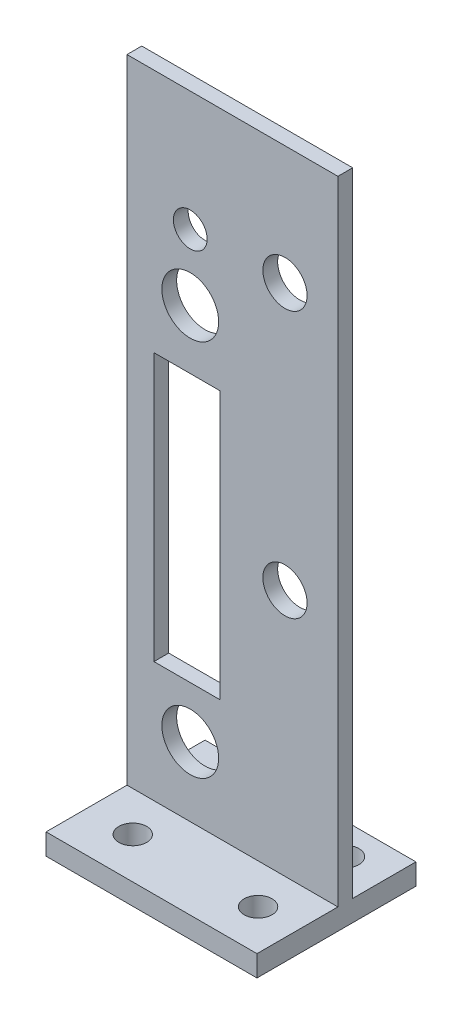
SolidWorks part; units mm, degrees
ref_plane "前视基准面" through (0, 0, 0) normal (0, 0, 1) x (1, 0, 0)
ref_plane "上视基准面" through (0, 0, 0) normal (0, 1, 0) x (1, 0, 0)
ref_plane "右视基准面" through (0, 0, 0) normal (1, 0, 0) x (0, 0, -1)
other "Configuration Table"
sketch "草图1" plane through (0, 0, 0) normal (0, 0, 1) x (1, 0, 0)
  line L1 (-23.3216, 41.8115) -> (26.6784, 41.8115)
  line L2 (-23.3216, 41.8115) -> (-23.3216, -108.1885)
  line L3 (-23.3216, -108.1885) -> (26.6784, -108.1885)
  line L4 (26.6784, 41.8115) -> (26.6784, -108.1885)
  dimension "D1" = 50
  dimension "D2" = 150
extrude "凸台-拉伸1" add sketch "草图1" along normal blind 3.5
sketch "草图5" plane through (0, 0, 3.5) normal (0, 0, 1) x (1, 0, 0)
  circle A0 centre (14.1357, 13.6492) radius 5.24
  circle A1 centre (14.1357, -49.4628) radius 5.24
  point P4 (14.1357, -14.9967)
  point P5 (14.1357, -49.4628)
  point P6 (14.1357, 13.6492)
sketch "草图8" plane through (0, -108.1885, 0) normal (0, -1, 0) x (1, 0, 0)
  line L0 (-23.3216, 0) -> (-23.3216, -15)
  line L2 (-23.3216, -15) -> (26.6784, -15)
  line L3 (-23.3216, -15) -> (-23.3216, 22.6855)
  line L4 (-23.3216, 22.6855) -> (26.6784, 22.6855)
  line L5 (26.6784, -15) -> (26.6784, 22.6855)
  line M6 (-23.3216, 0) -> (26.6784, 0)
  line M7 (26.6784, 0) -> (26.6784, 3.5)
  line M8 (26.6784, 3.5) -> (-23.3216, 3.5)
  line M9 (-23.3216, 3.5) -> (-23.3216, 0)
  dimension "D1" = 50
  dimension "D2" = 37.6855
extrude "凸台-拉伸3" add sketch "草图8" along normal blind 5 contours L2 L5 L0 M6 | M9 M6 M7 M8 | L5 L4 L3 M8
sketch "草图9" plane through (0, -108.1885, 0) normal (0, 1, 0) x (1, 0, 0)
  circle A0 centre (-12.5225, 7.6721) radius 3.302
  circle A1 centre (17.1873, 7.6721) radius 3.302
  circle A2 centre (-12.5225, -12.9285) radius 3.302
  circle A3 centre (17.1873, -12.9285) radius 3.302
  point P0 (-12.5225, -12.9285)
  point P1 (17.1873, -12.9285)
  point P2 (17.1873, 7.6721)
  point P3 (-12.5225, 7.6721)
extrude "切除-拉伸7" cut sketch "草图9" against normal blind 5
sketch "草图10" plane through (0, 0, 3.5) normal (0, 0, 1) x (1, 0, 0)
  line L0 (-23.3216, 41.8115) -> (-23.3216, -108.1885) construction
  line L2 (-16.9307, -16.1959) -> (-1.2434, -16.1959)
  line L3 (-16.9307, -16.1959) -> (-16.9307, -79.6262)
  line L4 (-16.9307, -79.6262) -> (-1.2434, -79.6262)
  line L5 (-1.2434, -16.1959) -> (-1.2434, -79.6262)
  circle A0 centre (-8.3216, -91.803) radius 6.731
  circle A1 centre (-8.3216, -2.203) radius 6.731
  circle A2 centre (-8.3216, 13.397) radius 4
  point P6 (-8.3216, -2.203)
  point P11 (-8.3216, 13.397)
  dimension "D1" = 15
  dimension "D3" = 15.6
  dimension "D2" = 89.6
extrude "切除-拉伸8" cut sketch "草图10" against normal blind 10
extrude "切除-拉伸9" cut sketch "草图5" against normal blind 10
